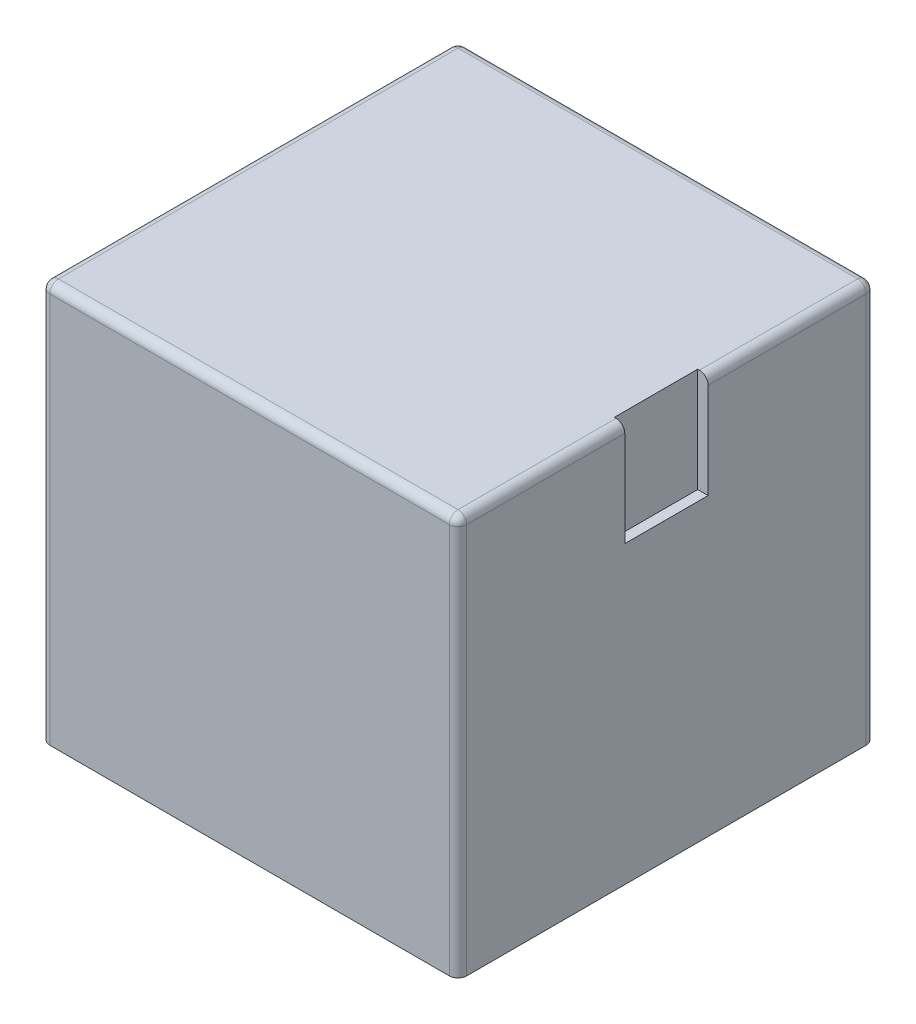
SolidWorks part; units mm, degrees
material "ABS"
ref_plane "Front Plane" through (0, 0, 0) normal (0, 0, 1) x (1, 0, 0)
ref_plane "Top Plane" through (0, 0, 0) normal (0, 1, 0) x (1, 0, 0)
ref_plane "Right Plane" through (0, 0, 0) normal (1, 0, 0) x (0, 0, -1)
sketch "Sketch1" plane through (0, 0, 0) normal (0, 1, 0) x (1, 0, 0)
  line L1 (-59.8866, 60) -> (60.1134, 60)
  line L2 (-59.8866, 60) -> (-59.8866, -60)
  line L3 (-59.8866, -60) -> (60.1134, -60)
  line L4 (60.1134, 60) -> (60.1134, -60)
  dimension "D1" = 120
  dimension "D2" = 120
extrude "Boss-Extrude1" add sketch "Sketch1" along normal blind 115
sketch "Sketch2" plane through (0, 0, 0) normal (0, -1, 0) x (1, 0, 0)
  line L0 (60.1134, -60) -> (-59.8866, -60) construction
  line L1 (55.1134, 55) -> (-54.8866, 55)
  line L2 (55.1134, 55) -> (55.1134, -55)
  line L3 (55.1134, -55) -> (-54.8866, -55)
  line L4 (-54.8866, 55) -> (-54.8866, -55)
  line L5 (-59.8866, -60) -> (-59.8866, 60) construction
  line L6 (-59.8866, 60) -> (60.1134, 60) construction
  line L7 (60.1134, 60) -> (60.1134, -60) construction
  dimension "D1" = 5
  dimension "D2" = 5
  dimension "D3" = 5
  dimension "D4" = 5
extrude "Cut-Extrude1" cut sketch "Sketch2" against normal blind 110
sketch "Sketch4" plane through (60.1134, 0, 0) normal (1, 0, 0) x (0, 0, -1)
  line L0 (-60, 115) -> (60, 115) construction
  line L1 (-12, 115) -> (12, 115)
  line L2 (-12, 115) -> (-12, 85)
  line L3 (-12, 85) -> (12, 85)
  line L4 (12, 115) -> (12, 85)
  line L6 (60, 115) -> (60, 0) construction
  line L7 (-60, 115) -> (-60, 0) construction
  dimension "D1" = 24
  dimension "D2" = 48
  dimension "D3" = 48
  dimension "D4" = 30
extrude "Cut-Extrude3" cut sketch "Sketch4" against normal blind 3
sketch "Sketch6" plane through (0, 0, -60) normal (0, 0, -1) x (-1, 0, 0)
  line L0 (-60.1134, 115) -> (-60.1134, 0) construction
  line L1 (-60.1134, 115) -> (59.8866, 115) construction
  circle A0 centre (-35.1134, 90) radius 7.75
  dimension "D1" = 25
  dimension "D2" = 25
extrude "Cut-Extrude5" cut sketch "Sketch6" against normal blind 6
sketch "Sketch9" plane through (55.1134, 0, 0) normal (-1, 0, 0) x (0, 0, 1)
  line L0 (-55, 110) -> (55, 110) construction
  line L1 (-15, 110) -> (15, 110)
  line L2 (-15, 110) -> (-15, 75)
  line L3 (-15, 75) -> (15, 75)
  line L4 (15, 110) -> (15, 75)
  line L5 (-55, 110) -> (-55, 0) construction
  line L6 (55, 110) -> (55, 0) construction
  dimension "D1" = 35
  dimension "D2" = 30
  dimension "D3" = 40
  dimension "D4" = 40
extrude "Boss-Extrude2" add sketch "Sketch9" along normal blind 3
fillet "Fillet2" radius 2.5 9 edges at (-59.8866, 115, 0) (-59.8866, 57.5, -60) (0.1134, 115, -60) (60.1134, 57.5, -60) (60.1134, 115, -36) (-59.8866, 57.5, 60) (0.1134, 115, 60) (60.1134, 115, 36) (60.1134, 57.5, 60)
sketch "Sketch12" plane through (-59.8866, 0, 0) normal (-1, 0, 0) x (0, 0, 1)
  line L1 (0, 100) -> (40, 100)
  line L2 (0, 100) -> (0, 50)
  line L3 (0, 50) -> (40, 50)
  line L4 (40, 100) -> (40, 50)
extrude "Cut-Extrude8" cut sketch "Sketch12" against normal blind 5
sketch "Sketch13" plane through (-59.8866, 0, 0) normal (-1, 0, 0) x (0, 0, 1)
  line L1 (-5, 105) -> (45, 105)
  line L2 (-5, 105) -> (-5, 45)
  line L3 (-5, 45) -> (45, 45)
  line L4 (45, 105) -> (45, 45)
extrude "Cut-Extrude9" cut sketch "Sketch13" against normal blind 3
sketch "Sketch14" plane through (-59.8866, 0, 0) normal (-1, 0, 0) x (0, 0, 1)
  line L1 (-10, 105) -> (-50, 105)
  line L2 (-10, 105) -> (-10, 45)
  line L3 (-10, 45) -> (-50, 45)
  line L4 (-50, 105) -> (-50, 45)
extrude "Cut-Extrude10" cut sketch "Sketch14" against normal blind 3
